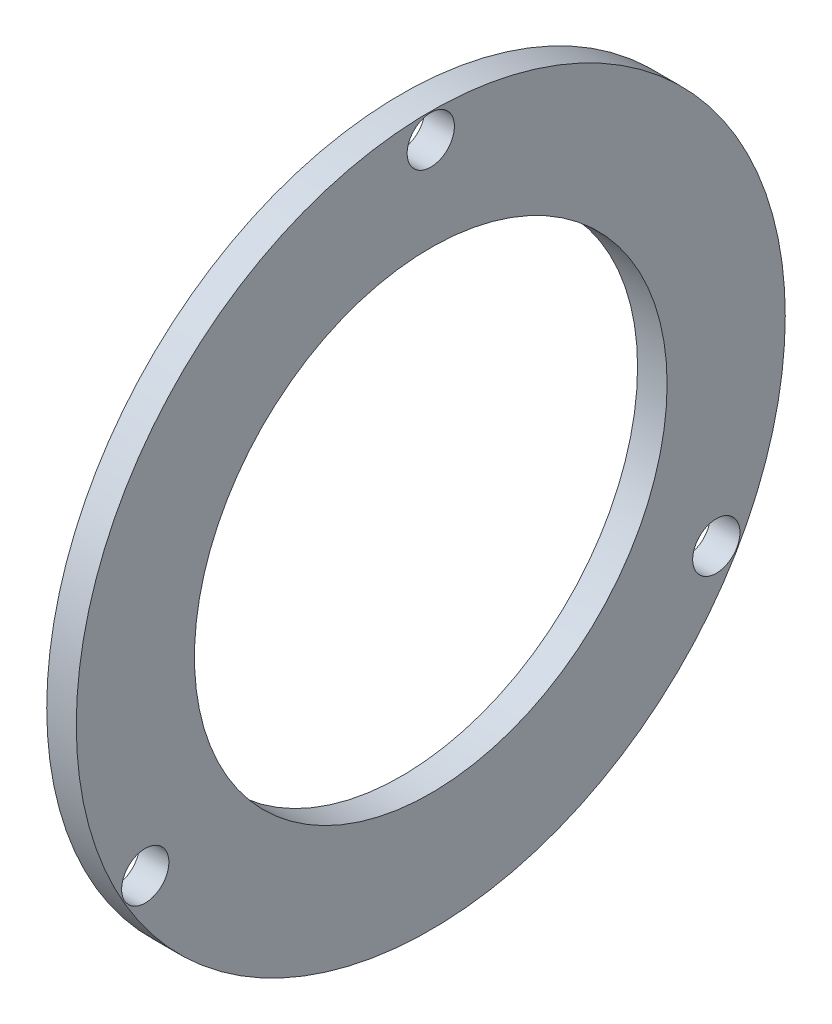
SolidWorks part; units mm, degrees
material "E-Glass Fiber"
ref_plane "Front Plane" through (0, 0, 0) normal (0, 0, 1) x (1, 0, 0)
ref_plane "Top Plane" through (0, 0, 0) normal (0, 1, 0) x (1, 0, 0)
ref_plane "Right Plane" through (0, 0, 0) normal (1, 0, 0) x (0, 0, -1)
sketch "Sketch1" plane through (0, 0, 0) normal (1, 0, 0) x (0, 0, -1)
  circle A0 centre (0, 0) radius 76.2
  circle A1 centre (0, 0) radius 50.8
  circle A2 centre (0, 70.866) radius 5.08
  circle A3 centre (61.3718, -35.433) radius 5.08
  circle A4 centre (-61.3718, -35.433) radius 5.08
  point P12 (0, 0)
  dimension "D1" = 152.4
  dimension "D2" = 101.6
  dimension "D3" = 10.16
  dimension "D4" = 70.866
  dimension "D5" = 3
extrude "Boss-Extrude1" add sketch "Sketch1" along normal blind 6.35
